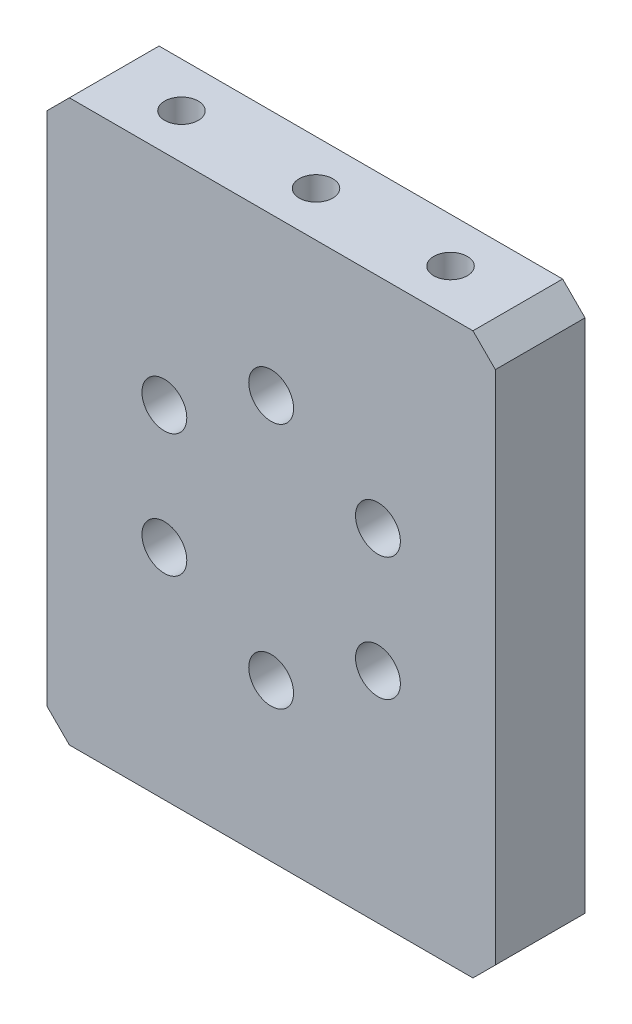
SolidWorks part; units mm, degrees
ref_plane "前视基准面" through (0, 0, 0) normal (0, 0, 1) x (1, 0, 0)
ref_plane "上视基准面" through (0, 0, 0) normal (0, 1, 0) x (1, 0, 0)
ref_plane "右视基准面" through (0, 0, 0) normal (1, 0, 0) x (0, 0, -1)
other "Configuration Table"
sketch "草图1" plane through (0, 0, 0) normal (0, 0, 1) x (1, 0, 0)
  line L1 (-20, 25) -> (20, 25)
  line L2 (-20, 25) -> (-20, -25)
  line L3 (-20, -25) -> (20, -25)
  line L4 (20, 25) -> (20, -25)
  line L5 (-20, 25) -> (20, -25) construction
  line L6 (-20, -25) -> (20, 25) construction
  point P0 (0, 0)
  dimension "D1" = 40
  dimension "D2" = 50
extrude "凸台-拉伸1" add sketch "草图1" along normal blind 8
sketch "草图2" plane through (0, 0, 0) normal (0, 0, -1) x (-1, 0, 0)
  circle A0 centre (0, 0) radius 15
  dimension "D1" = 30
extrude "切除-拉伸1" cut sketch "草图2" against normal blind 4
sketch "草图3" plane through (0, 0, 4) normal (0, 0, -1) x (-1, 0, 0)
  circle A0 centre (0, 11) radius 2
  circle A1 centre (9.5263, 5.5) radius 2
  circle A2 centre (9.5263, -5.5) radius 2
  circle A3 centre (0, -11) radius 2
  circle A4 centre (-9.5263, -5.5) radius 2
  circle A5 centre (-9.5263, 5.5) radius 2
  point P15 (0, 0)
  dimension "D1" = 4
  dimension "D2" = 11
  dimension "D3" = 6
extrude "切除-拉伸2" cut sketch "草图3" against normal blind 10
chamfer "倒角1" distance 2 angle 45 4 edges at (-20, -25, 4) (20, -25, 4) (-20, 25, 4) (20, 25, 4)
sketch "草图4" plane through (0, 25, 0) normal (0, 1, 0) x (1, 0, 0)
  line L0 (18, 0) -> (-18, 0) construction
  line L1 (-20, -8) -> (-20, 0) construction
  circle A0 centre (-12, -4) radius 1.5
  circle A1 centre (0, -4) radius 1.5
  circle A2 centre (12, -4) radius 1.5
  dimension "D1" = 3
  dimension "D2" = 4
  dimension "D3" = 8
  dimension "D4" = 2
  dimension "D5" = 2
extrude "切除-拉伸3" cut sketch "草图4" against normal blind 6
sketch "草图5" plane through (0, -25, 0) normal (0, -1, 0) x (1, 0, 0)
  line L0 (-18, 8) -> (18, 8) construction
  line L1 (-20, 0) -> (-20, 8) construction
  circle A0 centre (-12, 4) radius 1.5
  circle A1 centre (0, 4) radius 1.5
  circle A2 centre (12, 4) radius 1.5
  dimension "D1" = 3
  dimension "D2" = 4
  dimension "D3" = 8
  dimension "D4" = 2
  dimension "D5" = 2
extrude "切除-拉伸4" cut sketch "草图5" against normal blind 6
chamfer "倒角2" distance 0.5 angle 45 1 edges at (-15, 0, 0)
